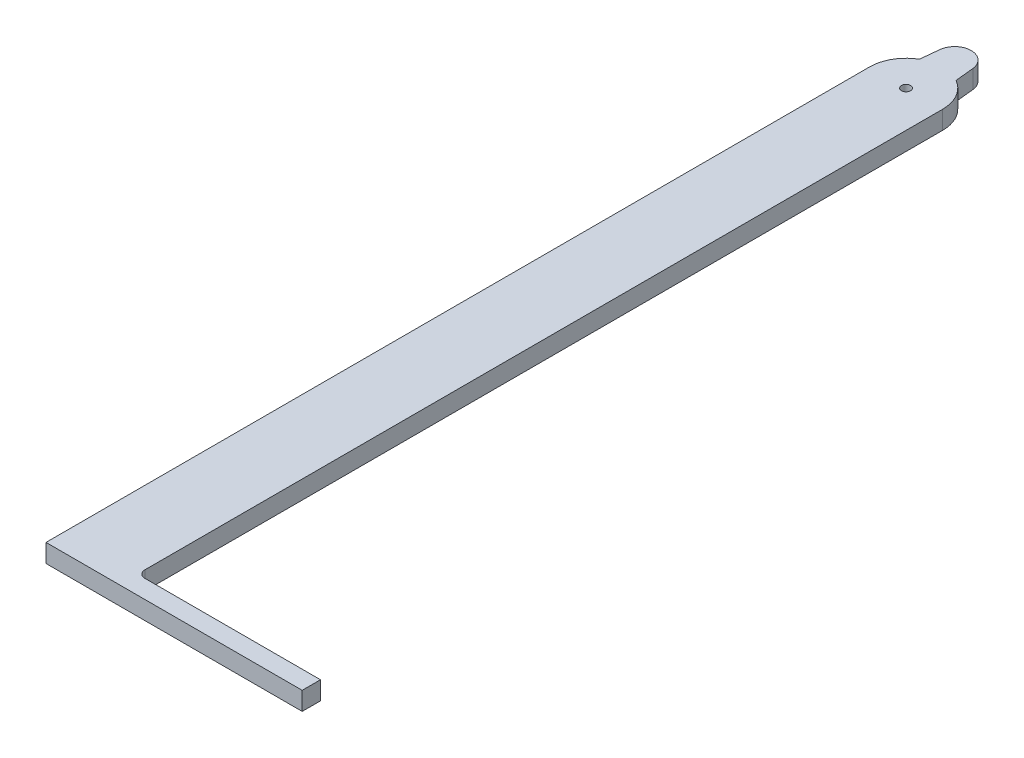
SolidWorks part; units mm, degrees
ref_plane "Front Plane" through (0, 0, 0) normal (0, 0, 1) x (1, 0, 0)
ref_plane "Top Plane" through (0, 0, 0) normal (0, 1, 0) x (1, 0, 0)
ref_plane "Right Plane" through (0, 0, 0) normal (1, 0, 0) x (0, 0, -1)
sketch "Sketch1" plane through (0, 0, 0) normal (0, 1, 0) x (1, 0, 0)
  line L1 (-12.7, 0) -> (12.7, 0)
  line L2 (-12.7, 0) -> (-12.7, -279.4)
  line L3 (-12.7, -279.4) -> (12.7, -279.4)
  line L4 (12.7, 0) -> (12.7, -279.4)
  circle A0 centre (0, 0) radius 12.7
  dimension "D1" = 25.4
  dimension "D2" = 279.4
extrude "Boss-Extrude1" add sketch "Sketch1" along normal blind 6.35 contours A0 L2 L3 L4 | L1 A0 | L1 A0
sketch "Sketch2" plane through (0, 6.35, 0) normal (0, 1, 0) x (1, 0, 0)
  line L1 (-12.7, -279.4) -> (76.2, -279.4)
  line L2 (-12.7, -279.4) -> (-12.7, -285.75)
  line L3 (-12.7, -285.75) -> (76.2, -285.75)
  line L4 (76.2, -279.4) -> (76.2, -285.75)
  dimension "D1" = 88.9
  dimension "D2" = 6.35
extrude "Boss-Extrude2" add sketch "Sketch2" against normal up to surface (6.35 mm away) up to face at (0, 0, 136.525)
fillet "Fillet1" radius 2.54 1 edges
sketch "Sketch3" plane through (0, 0, 0) normal (0, -1, 0) x (-1, 0, 0)
  line L4 (-7.3841, 1.2138) -> (7.3841, 1.2138)
  line L6 (-7.3841, 1.2138) -> (-5.6981, 17.4684)
  line L7 (5.6981, 17.4684) -> (7.3841, 1.2138)
  line L8 (-7.3841, 1.2138) -> (-5.6981, 17.4684)
  line L9 (5.6981, 17.4684) -> (7.3841, 1.2138)
  arc A3 (5.6981, 17.4684) -> (-5.6981, 17.4684) centre (0, 16.8774) ccw
  arc A4 (5.6981, 17.4684) -> (-5.6981, 17.4684) centre (0, 16.8774) ccw
  dimension "D1" = 3.175
extrude "Boss-Extrude3" add sketch "Sketch3" against normal up to surface (6.35 mm away) up to face at (28.2277, 6.35, 179.508)
sketch "Sketch4" plane through (0, 0, 0) normal (0, -1, 0) x (-1, 0, 0)
  circle A0 centre (0, 0) radius 1.5875
  dimension "D1" = 3.175
extrude "Cut-Extrude1" cut sketch "Sketch4" against normal through all
